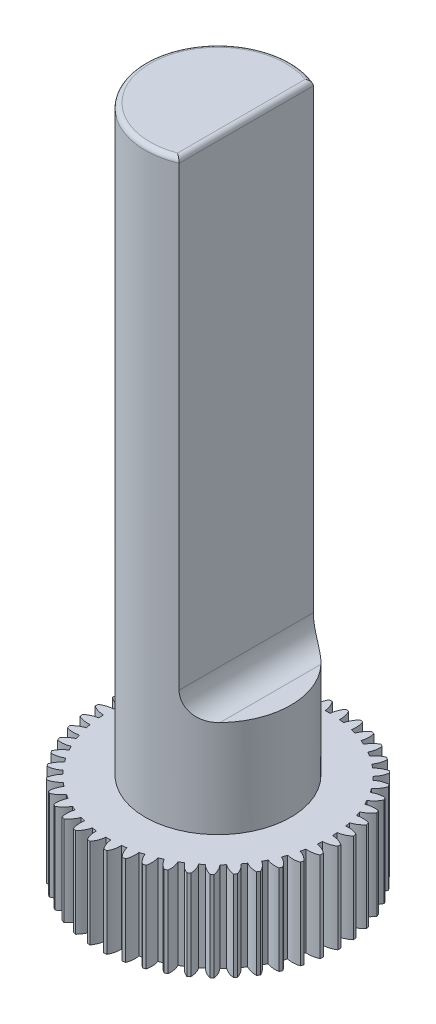
SolidWorks part; units mm, degrees
ref_plane "Front Plane" through (0, 0, 0) normal (0, 0, 1) x (1, 0, 0)
ref_plane "Top Plane" through (0, 0, 0) normal (0, 1, 0) x (1, 0, 0)
ref_plane "Right Plane" through (0, 0, 0) normal (1, 0, 0) x (0, 0, -1)
sketch "Sketch1" plane through (0, 0, 0) normal (0, 1, 0) x (1, 0, 0)
  line L0 (0, 2.5) -> (0, 3.8265) construction
  arc A0 (-2.12, 1.3251) -> (-2.1518, 1.2727) centre (0, 0) ccw
  arc A1 (-0.5614, 2.1892) -> (-0.6577, 2.1622) centre (0, 0) ccw
  arc A2 (0.05, 2.2594) -> (0.14, 2.4961) centre (0.511, 2.2195) cw
  arc A3 (-0.05, 2.2594) -> (-0.14, 2.4961) centre (-0.511, 2.2195) ccw
  arc A4 (0.3572, 2.2316) -> (0.4786, 2.4538) centre (0.8084, 2.1293) cw
  arc A5 (0.2581, 2.2452) -> (0.2012, 2.4919) centre (-0.204, 2.2685) ccw
  arc A6 (0.6577, 2.1622) -> (0.8082, 2.3657) centre (1.0909, 1.9994) cw
  arc A7 (0.5614, 2.1892) -> (0.5386, 2.4413) centre (0.1068, 2.2751) ccw
  arc A8 (0.946, 2.0525) -> (1.1228, 2.2337) centre (1.3529, 1.8322) cw
  arc A9 (0.8543, 2.0923) -> (0.866, 2.3452) centre (0.4156, 2.2394) ccw
  arc A10 (1.2167, 1.9045) -> (1.4165, 2.06) centre (1.5898, 1.6309) cw
  arc A11 (1.1313, 1.9565) -> (1.1773, 2.2054) centre (0.7167, 2.1619) ccw
  arc A12 (1.4647, 1.7211) -> (1.6838, 1.8479) centre (1.7971, 1.3993) cw
  arc A13 (1.3871, 1.7842) -> (1.4666, 2.0246) centre (1.0044, 2.0442) ccw
  arc A14 (1.6854, 1.5057) -> (1.9198, 1.6014) centre (1.9709, 1.1415) cw
  arc A15 (1.6172, 1.5787) -> (1.7287, 1.806) centre (1.2734, 1.8884) ccw
  arc A16 (1.8747, 1.2621) -> (2.12, 1.3251) centre (2.108, 0.8625) cw
  arc A17 (1.8171, 1.3438) -> (1.9585, 1.5538) centre (1.5186, 1.6974) ccw
  arc A18 (2.0291, 0.9951) -> (2.2806, 1.0241) centre (2.2058, 0.5674) cw
  arc A19 (1.9831, 1.0839) -> (2.1518, 1.2727) centre (1.7356, 1.4748) ccw
  arc A20 (2.1457, 0.7095) -> (2.3988, 0.704) centre (2.2625, 0.2618) cw
  arc A21 (2.1122, 0.8038) -> (2.3051, 0.9678) centre (1.9203, 1.2248) ccw
  arc A22 (2.2224, 0.4107) -> (2.4724, 0.3708) centre (2.2771, -0.0487) cw
  arc A23 (2.202, 0.5087) -> (2.4154, 0.6449) centre (2.0692, 0.9519) ccw
  arc A24 (2.2576, 0.1043) -> (2.4998, 0.0307) centre (2.2492, -0.3583) cw
  arc A25 (2.2508, 0.2041) -> (2.4807, 0.31) centre (2.1795, 0.6613) ccw
  arc A26 (2.2508, -0.2041) -> (2.4807, -0.31) centre (2.1795, -0.6613) cw
  arc A27 (2.2576, -0.1043) -> (2.4998, -0.0307) centre (2.2492, 0.3583) ccw
  arc A28 (2.202, -0.5087) -> (2.4154, -0.6449) centre (2.0692, -0.9519) cw
  arc A29 (2.2224, -0.4107) -> (2.4724, -0.3708) centre (2.2771, 0.0487) ccw
  arc A30 (2.1122, -0.8038) -> (2.3051, -0.9678) centre (1.9203, -1.2248) cw
  arc A31 (2.1457, -0.7095) -> (2.3988, -0.704) centre (2.2625, -0.2618) ccw
  arc A32 (1.9831, -1.0839) -> (2.1518, -1.2727) centre (1.7356, -1.4748) cw
  arc A33 (2.0291, -0.9951) -> (2.2806, -1.0241) centre (2.2058, -0.5674) ccw
  arc A34 (1.8171, -1.3438) -> (1.9585, -1.5538) centre (1.5186, -1.6974) cw
  arc A35 (1.8747, -1.2621) -> (2.12, -1.3251) centre (2.108, -0.8625) ccw
  arc A36 (1.6172, -1.5787) -> (1.7287, -1.806) centre (1.2734, -1.8884) cw
  arc A37 (1.6854, -1.5057) -> (1.9198, -1.6014) centre (1.9709, -1.1415) ccw
  arc A38 (1.3871, -1.7842) -> (1.4666, -2.0246) centre (1.0044, -2.0442) cw
  arc A39 (1.4647, -1.7211) -> (1.6838, -1.8479) centre (1.7971, -1.3993) ccw
  arc A40 (1.1313, -1.9565) -> (1.1773, -2.2054) centre (0.7167, -2.1619) cw
  arc A41 (1.2167, -1.9045) -> (1.4165, -2.06) centre (1.5898, -1.6309) ccw
  arc A42 (0.8543, -2.0923) -> (0.866, -2.3452) centre (0.4156, -2.2394) cw
  arc A43 (0.946, -2.0525) -> (1.1228, -2.2337) centre (1.3529, -1.8322) ccw
  arc A44 (0.5614, -2.1892) -> (0.5386, -2.4413) centre (0.1068, -2.2751) cw
  arc A45 (0.6577, -2.1622) -> (0.8082, -2.3657) centre (1.0909, -1.9994) ccw
  arc A46 (0.2581, -2.2452) -> (0.2012, -2.4919) centre (-0.204, -2.2685) cw
  arc A47 (0.3572, -2.2316) -> (0.4786, -2.4538) centre (0.8084, -2.1293) ccw
  arc A48 (-0.05, -2.2594) -> (-0.14, -2.4961) centre (-0.511, -2.2195) cw
  arc A49 (0.05, -2.2594) -> (0.14, -2.4961) centre (0.511, -2.2195) ccw
  arc A50 (-0.3572, -2.2316) -> (-0.4786, -2.4538) centre (-0.8084, -2.1293) cw
  arc A51 (-0.2581, -2.2452) -> (-0.2012, -2.4919) centre (0.204, -2.2685) ccw
  arc A52 (-0.6577, -2.1622) -> (-0.8082, -2.3657) centre (-1.0909, -1.9994) cw
  arc A53 (-0.5614, -2.1892) -> (-0.5386, -2.4413) centre (-0.1068, -2.2751) ccw
  arc A54 (-0.946, -2.0525) -> (-1.1228, -2.2337) centre (-1.3529, -1.8322) cw
  arc A55 (-0.8543, -2.0923) -> (-0.866, -2.3452) centre (-0.4156, -2.2394) ccw
  arc A56 (-1.2167, -1.9045) -> (-1.4165, -2.06) centre (-1.5898, -1.6309) cw
  arc A57 (-1.1313, -1.9565) -> (-1.1773, -2.2054) centre (-0.7167, -2.1619) ccw
  arc A58 (-1.4647, -1.7211) -> (-1.6838, -1.8479) centre (-1.7971, -1.3993) cw
  arc A59 (-1.3871, -1.7842) -> (-1.4666, -2.0246) centre (-1.0044, -2.0442) ccw
  arc A60 (-1.6854, -1.5057) -> (-1.9198, -1.6014) centre (-1.9709, -1.1415) cw
  arc A61 (-1.6172, -1.5787) -> (-1.7287, -1.806) centre (-1.2734, -1.8884) ccw
  arc A62 (-1.8747, -1.2621) -> (-2.12, -1.3251) centre (-2.108, -0.8625) cw
  arc A63 (-1.8171, -1.3438) -> (-1.9585, -1.5538) centre (-1.5186, -1.6974) ccw
  arc A64 (-2.0291, -0.9951) -> (-2.2806, -1.0241) centre (-2.2058, -0.5674) cw
  arc A65 (-1.9831, -1.0839) -> (-2.1518, -1.2727) centre (-1.7356, -1.4748) ccw
  arc A66 (-2.1457, -0.7095) -> (-2.3988, -0.704) centre (-2.2625, -0.2618) cw
  arc A67 (-2.1122, -0.8038) -> (-2.3051, -0.9678) centre (-1.9203, -1.2248) ccw
  arc A68 (-2.2224, -0.4107) -> (-2.4724, -0.3708) centre (-2.2771, 0.0487) cw
  arc A69 (-2.202, -0.5087) -> (-2.4154, -0.6449) centre (-2.0692, -0.9519) ccw
  arc A70 (-2.2576, -0.1043) -> (-2.4998, -0.0307) centre (-2.2492, 0.3583) cw
  arc A71 (-2.2508, -0.2041) -> (-2.4807, -0.31) centre (-2.1795, -0.6613) ccw
  arc A72 (-2.2508, 0.2041) -> (-2.4807, 0.31) centre (-2.1795, 0.6613) cw
  arc A73 (-2.2576, 0.1043) -> (-2.4998, 0.0307) centre (-2.2492, -0.3583) ccw
  arc A74 (-2.202, 0.5087) -> (-2.4154, 0.6449) centre (-2.0692, 0.9519) cw
  arc A75 (-2.2224, 0.4107) -> (-2.4724, 0.3708) centre (-2.2771, -0.0487) ccw
  arc A76 (-2.1122, 0.8038) -> (-2.3051, 0.9678) centre (-1.9203, 1.2248) cw
  arc A77 (-2.1457, 0.7095) -> (-2.3988, 0.704) centre (-2.2625, 0.2618) ccw
  arc A78 (-1.9831, 1.0839) -> (-2.1518, 1.2727) centre (-1.7356, 1.4748) cw
  arc A79 (-2.0291, 0.9951) -> (-2.2806, 1.0241) centre (-2.2058, 0.5674) ccw
  arc A80 (-1.8171, 1.3438) -> (-1.9585, 1.5538) centre (-1.5186, 1.6974) cw
  arc A81 (-1.8747, 1.2621) -> (-2.12, 1.3251) centre (-2.108, 0.8625) ccw
  arc A82 (-1.6172, 1.5787) -> (-1.7287, 1.806) centre (-1.2734, 1.8884) cw
  arc A83 (-1.6854, 1.5057) -> (-1.9198, 1.6014) centre (-1.9709, 1.1415) ccw
  arc A84 (-1.3871, 1.7842) -> (-1.4666, 2.0246) centre (-1.0044, 2.0442) cw
  arc A85 (-1.4647, 1.7211) -> (-1.6838, 1.8479) centre (-1.7971, 1.3993) ccw
  arc A86 (-1.1313, 1.9565) -> (-1.1773, 2.2054) centre (-0.7167, 2.1619) cw
  arc A87 (-1.2167, 1.9045) -> (-1.4165, 2.06) centre (-1.5898, 1.6309) ccw
  arc A88 (-0.8543, 2.0923) -> (-0.866, 2.3452) centre (-0.4156, 2.2394) cw
  arc A89 (-0.946, 2.0525) -> (-1.1228, 2.2337) centre (-1.3529, 1.8322) ccw
  arc A90 (-0.5614, 2.1892) -> (-0.5386, 2.4413) centre (-0.1068, 2.2751) cw
  arc A91 (-0.6577, 2.1622) -> (-0.8082, 2.3657) centre (-1.0909, 1.9994) ccw
  arc A92 (-0.2581, 2.2452) -> (-0.2012, 2.4919) centre (0.204, 2.2685) cw
  arc A93 (-0.3572, 2.2316) -> (-0.4786, 2.4538) centre (-0.8084, 2.1293) ccw
  arc A94 (-0.8543, 2.0923) -> (-0.946, 2.0525) centre (0, 0) ccw
  arc A95 (-1.1313, 1.9565) -> (-1.2167, 1.9045) centre (0, 0) ccw
  arc A96 (-1.3871, 1.7842) -> (-1.4647, 1.7211) centre (0, 0) ccw
  arc A97 (-1.6172, 1.5787) -> (-1.6854, 1.5057) centre (0, 0) ccw
  arc A98 (-1.8171, 1.3438) -> (-1.8747, 1.2621) centre (0, 0) ccw
  arc A99 (-0.2581, 2.2452) -> (-0.3572, 2.2316) centre (0, 0) ccw
  arc A100 (0.05, 2.2594) -> (-0.05, 2.2594) centre (0, 0) ccw
  arc A101 (0.3572, 2.2316) -> (0.2581, 2.2452) centre (0, 0) ccw
  arc A102 (0.6577, 2.1622) -> (0.5614, 2.1892) centre (0, 0) ccw
  arc A103 (0.946, 2.0525) -> (0.8543, 2.0923) centre (0, 0) ccw
  arc A104 (1.2167, 1.9045) -> (1.1313, 1.9565) centre (0, 0) ccw
  arc A105 (1.4647, 1.7211) -> (1.3871, 1.7842) centre (0, 0) ccw
  arc A106 (1.6854, 1.5057) -> (1.6172, 1.5787) centre (0, 0) ccw
  arc A107 (1.8747, 1.2621) -> (1.8171, 1.3438) centre (0, 0) ccw
  arc A108 (2.0291, 0.9951) -> (1.9831, 1.0839) centre (0, 0) ccw
  arc A109 (2.1457, 0.7095) -> (2.1122, 0.8038) centre (0, 0) ccw
  arc A110 (2.2224, 0.4107) -> (2.202, 0.5087) centre (0, 0) ccw
  arc A111 (2.2576, 0.1043) -> (2.2508, 0.2041) centre (0, 0) ccw
  arc A112 (2.2508, -0.2041) -> (2.2576, -0.1043) centre (0, 0) ccw
  arc A113 (2.202, -0.5087) -> (2.2224, -0.4107) centre (0, 0) ccw
  arc A114 (2.1122, -0.8038) -> (2.1457, -0.7095) centre (0, 0) ccw
  arc A115 (1.9831, -1.0839) -> (2.0291, -0.9951) centre (0, 0) ccw
  arc A116 (1.8171, -1.3438) -> (1.8747, -1.2621) centre (0, 0) ccw
  arc A117 (1.6172, -1.5787) -> (1.6854, -1.5057) centre (0, 0) ccw
  arc A118 (1.3871, -1.7842) -> (1.4647, -1.7211) centre (0, 0) ccw
  arc A119 (1.1313, -1.9565) -> (1.2167, -1.9045) centre (0, 0) ccw
  arc A120 (0.8543, -2.0923) -> (0.946, -2.0525) centre (0, 0) ccw
  arc A121 (0.5614, -2.1892) -> (0.6577, -2.1622) centre (0, 0) ccw
  arc A122 (0.2581, -2.2452) -> (0.3572, -2.2316) centre (0, 0) ccw
  arc A123 (-0.05, -2.2594) -> (0.05, -2.2594) centre (0, 0) ccw
  arc A124 (-0.3572, -2.2316) -> (-0.2581, -2.2452) centre (0, 0) ccw
  arc A125 (-0.6577, -2.1622) -> (-0.5614, -2.1892) centre (0, 0) ccw
  arc A126 (-0.946, -2.0525) -> (-0.8543, -2.0923) centre (0, 0) ccw
  arc A127 (-1.2167, -1.9045) -> (-1.1313, -1.9565) centre (0, 0) ccw
  arc A128 (-1.4647, -1.7211) -> (-1.3871, -1.7842) centre (0, 0) ccw
  arc A129 (-1.6854, -1.5057) -> (-1.6172, -1.5787) centre (0, 0) ccw
  arc A130 (-1.8747, -1.2621) -> (-1.8171, -1.3438) centre (0, 0) ccw
  arc A131 (-2.0291, -0.9951) -> (-1.9831, -1.0839) centre (0, 0) ccw
  arc A132 (-1.9831, 1.0839) -> (-2.0291, 0.9951) centre (0, 0) ccw
  arc A133 (-2.1122, 0.8038) -> (-2.1457, 0.7095) centre (0, 0) ccw
  arc A134 (-2.202, 0.5087) -> (-2.2224, 0.4107) centre (0, 0) ccw
  arc A135 (-2.2508, 0.2041) -> (-2.2576, 0.1043) centre (0, 0) ccw
  arc A136 (-2.2224, -0.4107) -> (-2.202, -0.5087) centre (0, 0) ccw
  arc A137 (-2.2576, -0.1043) -> (-2.2508, -0.2041) centre (0, 0) ccw
  arc A138 (-2.1457, -0.7095) -> (-2.1122, -0.8038) centre (0, 0) ccw
  arc A139 (-2.2806, 1.0241) -> (-2.3051, 0.9678) centre (0, 0) ccw
  arc A140 (-2.3988, 0.704) -> (-2.4154, 0.6449) centre (0, 0) ccw
  arc A141 (-2.4724, 0.3708) -> (-2.4807, 0.31) centre (0, 0) ccw
  arc A142 (-2.4998, 0.0307) -> (-2.4998, -0.0307) centre (0, 0) ccw
  arc A143 (-2.4807, -0.31) -> (-2.4724, -0.3708) centre (0, 0) ccw
  arc A144 (-2.4154, -0.6449) -> (-2.3988, -0.704) centre (0, 0) ccw
  arc A145 (-2.3051, -0.9678) -> (-2.2806, -1.0241) centre (0, 0) ccw
  arc A146 (-2.1518, -1.2727) -> (-2.12, -1.3251) centre (0, 0) ccw
  arc A147 (-1.9585, -1.5538) -> (-1.9198, -1.6014) centre (0, 0) ccw
  arc A148 (-1.7287, -1.806) -> (-1.6838, -1.8479) centre (0, 0) ccw
  arc A149 (-1.4666, -2.0246) -> (-1.4165, -2.06) centre (0, 0) ccw
  arc A150 (-1.1773, -2.2054) -> (-1.1228, -2.2337) centre (0, 0) ccw
  arc A151 (-0.866, -2.3452) -> (-0.8082, -2.3657) centre (0, 0) ccw
  arc A152 (-0.5386, -2.4413) -> (-0.4786, -2.4538) centre (0, 0) ccw
  arc A153 (-0.2012, -2.4919) -> (-0.14, -2.4961) centre (0, 0) ccw
  arc A154 (0.14, -2.4961) -> (0.2012, -2.4919) centre (0, 0) ccw
  arc A155 (0.4786, -2.4538) -> (0.5386, -2.4413) centre (0, 0) ccw
  arc A156 (0.8082, -2.3657) -> (0.866, -2.3452) centre (0, 0) ccw
  arc A157 (1.1228, -2.2337) -> (1.1773, -2.2054) centre (0, 0) ccw
  arc A158 (1.4165, -2.06) -> (1.4666, -2.0246) centre (0, 0) ccw
  arc A159 (1.6838, -1.8479) -> (1.7287, -1.806) centre (0, 0) ccw
  arc A160 (1.9198, -1.6014) -> (1.9585, -1.5538) centre (0, 0) ccw
  arc A161 (2.12, -1.3251) -> (2.1518, -1.2727) centre (0, 0) ccw
  arc A162 (2.2806, -1.0241) -> (2.3051, -0.9678) centre (0, 0) ccw
  arc A163 (2.3988, -0.704) -> (2.4154, -0.6449) centre (0, 0) ccw
  arc A164 (2.4724, -0.3708) -> (2.4807, -0.31) centre (0, 0) ccw
  arc A165 (2.4998, -0.0307) -> (2.4998, 0.0307) centre (0, 0) ccw
  arc A166 (2.4807, 0.31) -> (2.4724, 0.3708) centre (0, 0) ccw
  arc A167 (2.4154, 0.6449) -> (2.3988, 0.704) centre (0, 0) ccw
  arc A168 (2.3051, 0.9678) -> (2.2806, 1.0241) centre (0, 0) ccw
  arc A169 (2.1518, 1.2727) -> (2.12, 1.3251) centre (0, 0) ccw
  arc A170 (1.9585, 1.5538) -> (1.9198, 1.6014) centre (0, 0) ccw
  arc A171 (1.7287, 1.806) -> (1.6838, 1.8479) centre (0, 0) ccw
  arc A172 (1.4666, 2.0246) -> (1.4165, 2.06) centre (0, 0) ccw
  arc A173 (0.866, 2.3452) -> (0.8082, 2.3657) centre (0, 0) ccw
  arc A174 (1.1773, 2.2054) -> (1.1228, 2.2337) centre (0, 0) ccw
  arc A175 (0.5386, 2.4413) -> (0.4786, 2.4538) centre (0, 0) ccw
  arc A176 (0.2012, 2.4919) -> (0.14, 2.4961) centre (0, 0) ccw
  arc A177 (-0.14, 2.4961) -> (-0.2012, 2.4919) centre (0, 0) ccw
  arc A178 (-0.4786, 2.4538) -> (-0.5386, 2.4413) centre (0, 0) ccw
  arc A179 (-0.8082, 2.3657) -> (-0.866, 2.3452) centre (0, 0) ccw
  arc A180 (-1.1228, 2.2337) -> (-1.1773, 2.2054) centre (0, 0) ccw
  arc A181 (-1.4165, 2.06) -> (-1.4666, 2.0246) centre (0, 0) ccw
  arc A182 (-1.6838, 1.8479) -> (-1.7287, 1.806) centre (0, 0) ccw
  arc A183 (-1.9198, 1.6014) -> (-1.9585, 1.5538) centre (0, 0) ccw
  point P4 (0, 2.26)
  point P5 (0, 2.5)
  point P291 (0, 0)
  dimension "D1" = 5
  dimension "D2" = 0.24
  dimension "D3" = 0.05
  dimension "D4" = 0.14
  dimension "D5" = 46
extrude "Boss-Extrude1" add sketch "Sketch1" along normal blind 1.85
sketch "Sketch2" plane through (0, 0, 0) normal (0, -1, 0) x (1, 0, 0)
  circle A0 centre (0, 0) radius 0.5
  dimension "D1" = 1
extrude "Cut-Extrude1" cut sketch "Sketch2" against normal blind 1
sketch "Sketch3" plane through (0, 1.85, 0) normal (0, 1, 0) x (1, 0, 0)
  circle A0 centre (0, 0) radius 1.5
  dimension "D1" = 3
extrude "Boss-Extrude2" add sketch "Sketch3" along normal blind 12
sketch "Sketch4" plane through (0, 13.85, 0) normal (0, 1, 0) x (1, 0, 0)
  line L1 (1.7163, 1.6131) -> (0.5807, 1.6131)
  line L2 (1.7163, 1.6131) -> (1.7163, -1.8325)
  line L3 (1.7163, -1.8325) -> (0.5807, -1.8325)
  line L4 (0.5807, 1.6131) -> (0.5807, -1.8325)
extrude "Cut-Extrude2" cut sketch "Sketch4" against normal blind 10
fillet "Redondeo1" radius 0.5 1 edges at (0.5807, 3.85, 0)
fillet "Redondeo2" radius 0.1 2 edges at (-1.5, 13.85, 0) (0.5807, 13.85, 0)
